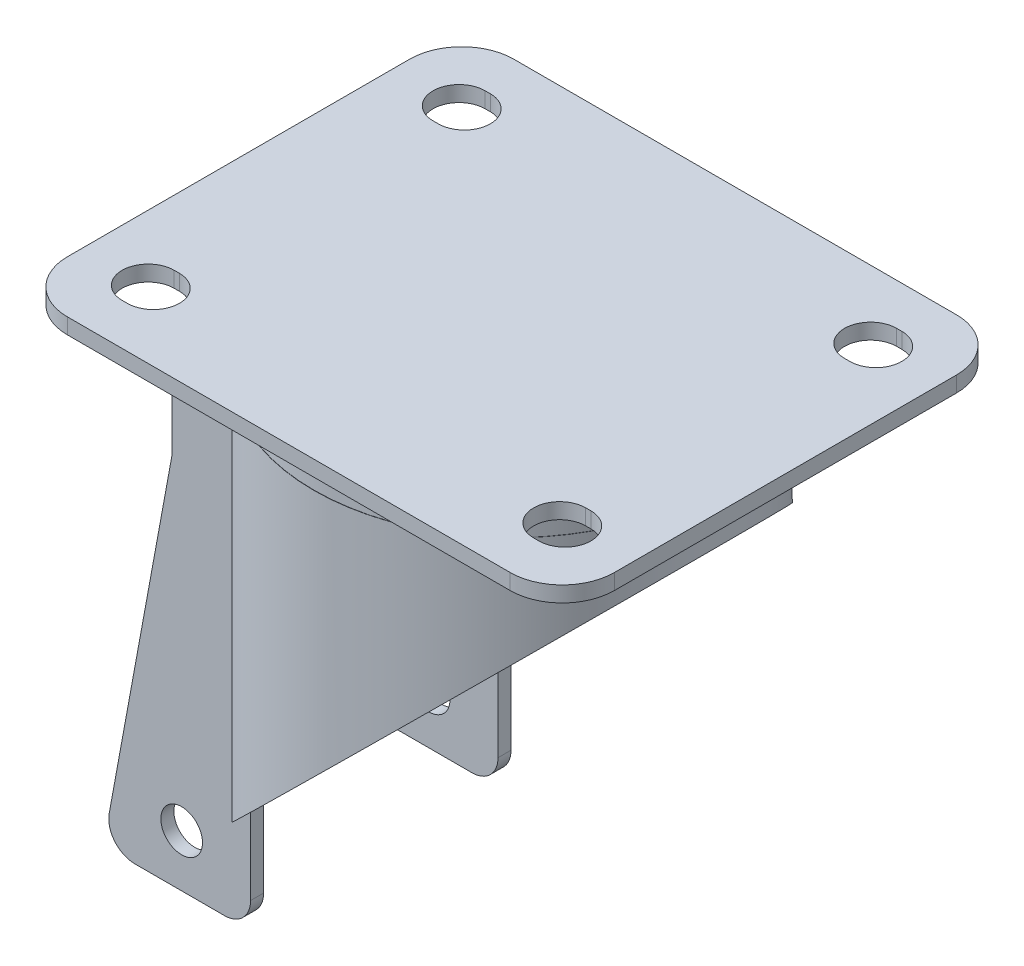
SolidWorks part; units mm, degrees
ref_plane "Спереди" through (0, 0, 0) normal (0, 0, 1) x (1, 0, 0)
ref_plane "Сверху" through (0, 0, 0) normal (0, 1, 0) x (1, 0, 0)
ref_plane "Справа" through (0, 0, 0) normal (1, 0, 0) x (0, 0, -1)
sketch "Эскиз1" plane through (0, 0, 0) normal (0, 1, 0) x (1, 0, 0)
  line L0 (40.0034, 29.8469) -> (39.0034, 29.8469) construction
  line L1 (-42.5034, 42.8469) -> (42.5034, 42.8469)
  line L2 (-52.5034, 32.8469) -> (-52.5034, -32.8469)
  line L3 (-42.5034, -42.8469) -> (42.5034, -42.8469)
  line L4 (52.5034, 32.8469) -> (52.5034, -32.8469)
  line L5 (-52.5034, 42.8469) -> (52.5034, -42.8469) construction
  line L6 (-52.5034, -42.8469) -> (52.5034, 42.8469) construction
  line L7 (40.0034, 24.8469) -> (39.0034, 24.8469)
  line L8 (40.0034, 34.8469) -> (39.0034, 34.8469)
  line L10 (-40.0034, 29.8469) -> (-39.0034, 29.8469) construction
  line L11 (-40.0034, 24.8469) -> (-39.0034, 24.8469)
  line L12 (-40.0034, 34.8469) -> (-39.0034, 34.8469)
  line L14 (40.0034, -29.8469) -> (39.0034, -29.8469) construction
  line L15 (40.0034, -24.8469) -> (39.0034, -24.8469)
  line L16 (40.0034, -34.8469) -> (39.0034, -34.8469)
  line L17 (-40.0034, -29.8469) -> (-39.0034, -29.8469) construction
  line L18 (-40.0034, -24.8469) -> (-39.0034, -24.8469)
  line L19 (-40.0034, -34.8469) -> (-39.0034, -34.8469)
  arc A0 (-42.5034, 42.8469) -> (-52.5034, 32.8469) centre (-42.5034, 32.8469) ccw
  arc A1 (52.5034, 32.8469) -> (42.5034, 42.8469) centre (42.5034, 32.8469) ccw
  arc A2 (42.5034, -42.8469) -> (52.5034, -32.8469) centre (42.5034, -32.8469) ccw
  arc A3 (-52.5034, -32.8469) -> (-42.5034, -42.8469) centre (-42.5034, -32.8469) ccw
  arc A4 (40.0034, 24.8469) -> (40.0034, 34.8469) centre (40.0034, 29.8469) ccw
  arc A5 (39.0034, 34.8469) -> (39.0034, 24.8469) centre (39.0034, 29.8469) ccw
  arc A6 (-40.0034, 24.8469) -> (-40.0034, 34.8469) centre (-40.0034, 29.8469) cw
  arc A7 (-39.0034, 34.8469) -> (-39.0034, 24.8469) centre (-39.0034, 29.8469) cw
  arc A8 (40.0034, -24.8469) -> (40.0034, -34.8469) centre (40.0034, -29.8469) cw
  arc A9 (39.0034, -34.8469) -> (39.0034, -24.8469) centre (39.0034, -29.8469) cw
  arc A10 (-40.0034, -24.8469) -> (-40.0034, -34.8469) centre (-40.0034, -29.8469) ccw
  arc A11 (-39.0034, -34.8469) -> (-39.0034, -24.8469) centre (-39.0034, -29.8469) ccw
  point P0 (0, 0)
  point P20 (39.5034, 29.8469)
  point P29 (-39.5034, 29.8469)
  point P38 (39.5034, -29.8469)
  point P45 (-39.5034, -29.8469)
  dimension "D1" = 10
extrude "Вытянуть1" add sketch "Эскиз1" along normal blind 3
sketch "Эскиз2" plane through (0, 0, 0) normal (0, -1, 0) x (1, 0, 0)
  circle A0 centre (0, 0) radius 38
  dimension "D1" = 76
extrude "Вытянуть2" add sketch "Эскиз2" along normal blind 7
sketch "Эскиз3" plane through (0, -7, 0) normal (0, -1, 0) x (1, 0, 0)
  circle A0 centre (0, 0) radius 35.5
  dimension "D1" = 71
extrude "Вытянуть-Тонкостенный1" add sketch "Эскиз3" along normal blind 85 thin
sketch "Эскиз4" plane through (0, 0, 0) normal (0, 0, 1) x (1, 0, 0)
  line L0 (46.0572, -9.1807) -> (-39.3369, -93.4753)
  line L4 (-39.3369, -93.4753) -> (46.0572, -93.4753)
  line L5 (46.0572, -93.4753) -> (46.0572, -9.1807)
  dimension "D1" = 46.0572
  dimension "D2" = 39.3369
  dimension "D3" = 9.1807
  dimension "D4" = 93.4753
extrude "Вытянуть3" cut sketch "Эскиз4" against normal mid plane 87
sketch "Эскиз5" plane through (0, 0, 0) normal (1, 0, 0) x (0, 0, -1)
  line L1 (24.25, -105.3823) -> (-25.75, -105.3823)
  line L2 (24.25, -105.3823) -> (24.25, -11.3823)
  line L3 (24.25, -11.3823) -> (-25.75, -11.3823)
  line L4 (-25.75, -105.3823) -> (-25.75, -11.3823)
  line L5 (24.25, -105.3823) -> (-25.75, -11.3823) construction
  line L6 (24.25, -11.3823) -> (-25.75, -105.3823) construction
  point P0 (-0.75, -58.3823)
  dimension "D1" = 25
  dimension "D2" = 47
extrude "Вытянуть4" cut sketch "Эскиз5" against normal blind 47
sketch "Эскиз6" plane through (0, -11.3823, 0) normal (0, -1, 0) x (1, 0, 0)
  line L2 (-38.6083, 25.75) -> (-24.4374, 25.75)
  line L3 (-39.5715, -24.25) -> (-25.9266, -24.25)
  arc A0 (-24.4374, 25.75) -> (-25.9266, -24.25) centre (0, 0) ccw
  arc A1 (-38.6083, 25.75) -> (-39.5715, -24.25) centre (-0.16, 0) ccw
extrude "Вытянуть5" add sketch "Эскиз6" along normal blind 2.5
fillet "Скругление1" radius 1 1 edges at (-38.037, -11.3823, 0.9951)
sketch "Эскиз8" plane through (0, 0, -24.25) normal (0, 0, -1) x (-1, 0, 0)
  line L0 (24.4374, -13.8823) -> (24.4374, -93.5624)
  line L1 (29.4374, -98.5624) -> (46.6678, -98.5624)
  line L3 (51.5854, -92.6583) -> (39.5715, -27.3157)
  line L4 (39.5715, -27.3157) -> (39.5715, -13.8823)
  line L5 (39.5715, -13.8823) -> (24.4374, -13.8823)
  arc A1 (29.4374, -98.5624) -> (24.4374, -93.5624) centre (29.4374, -93.5624) cw
  arc A2 (51.5854, -92.6583) -> (46.6678, -98.5624) centre (46.6678, -93.5624) cw
  dimension "D1" = 5
  dimension "D2" = 5
extrude "Вытянуть11" add sketch "Эскиз8" along normal blind 2.5 from offset 2.5 separate body
sketch "Эскиз10" plane through (0, 0, 25.75) normal (0, 0, 1) x (1, 0, 0)
  line L0 (-24.4374, -13.8823) -> (-24.4374, -93.5624)
  line L2 (-24.4374, -13.8823) -> (-39.5715, -13.8823)
  line L3 (-39.5715, -13.8823) -> (-39.5715, -27.3157)
  line L4 (-39.5715, -27.3157) -> (-51.5876, -92.6702)
  line L5 (-46.67, -98.5743) -> (-29.4374, -98.5743)
  arc A0 (-46.67, -98.5743) -> (-51.5876, -92.6702) centre (-46.67, -93.5743) cw
  arc A1 (-29.4374, -98.5743) -> (-24.4374, -93.5624) centre (-29.4374, -93.5743) ccw
  arc A2 (-29.4374, -98.5624) -> (-24.4374, -93.5624) centre (-29.4374, -93.5624) ccw construction
  point P12 (-52.6731, -98.5743)
  point P15 (-29.9258, -98.5743)
  dimension "D1" = 5
extrude "Вытянуть13" add sketch "Эскиз10" along normal blind 2.5 from offset 2.5 separate body
sketch "Эскиз11" plane through (0, 0, 0) normal (0, 0, 1) x (1, 0, 0)
  line L0 (-36.7463, -98.5743) -> (5.9951, -98.5743) construction
  line L2 (-16.5243, -88.5743) -> (12.252, -88.5743) construction
  line L3 (-51.67, -93.5743) -> (-51.67, -62.1048) construction
  line L4 (-37.67, -24.0185) -> (-37.67, -37.7013) construction
  line L5 (-37.67, -92.5743) -> (-61.2405, -92.5743) construction
  line L6 (-41.67, -88.5743) -> (-41.67, -43.0616) construction
  circle A1 centre (-37.67, -88.5743) radius 4
  dimension "D1" = 14
extrude "Вытянуть14" cut sketch "Эскиз11" against normal mid plane 72.5
